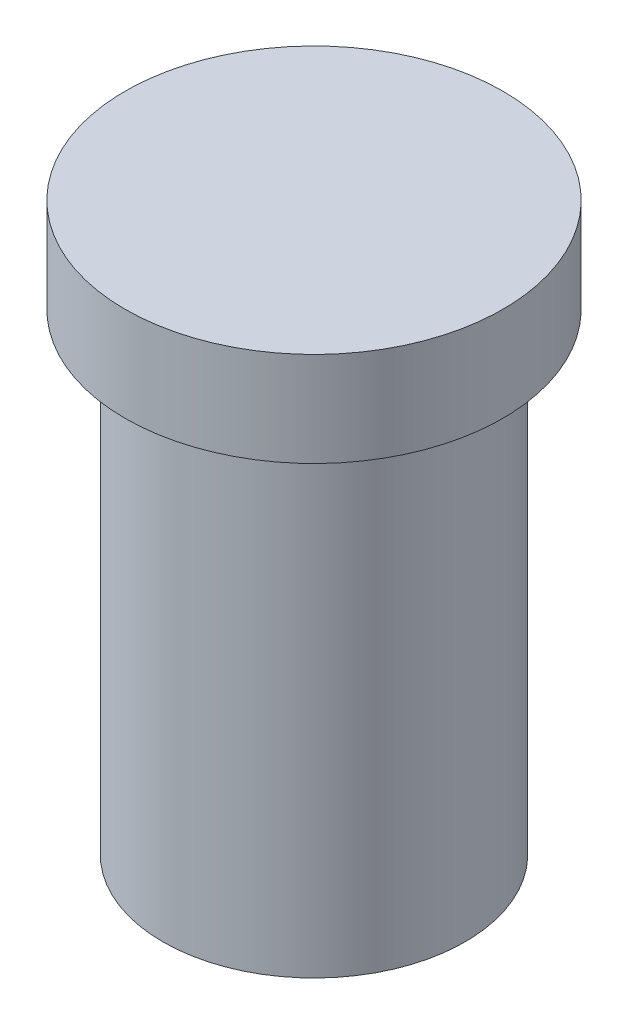
SolidWorks part; units mm, degrees
ref_plane "Front" through (0, 0, 0) normal (0, 0, 1) x (1, 0, 0)
ref_plane "Top" through (0, 0, 0) normal (0, 1, 0) x (1, 0, 0)
ref_plane "Right" through (0, 0, 0) normal (1, 0, 0) x (0, 0, -1)
sketch "Sketch1" plane through (0, 0, 0) normal (0, 1, 0) x (1, 0, 0)
  circle A0 centre (0, 0) radius 400
extrude "Boss-Extrude1" add sketch "Sketch1" along normal blind 1250
sketch "Sketch2" plane through (0, 1250, 0) normal (0, 1, 0) x (1, 0, 0)
  circle A0 centre (0, 0) radius 500
extrude "Boss-Extrude2" add sketch "Sketch2" along normal blind 250
